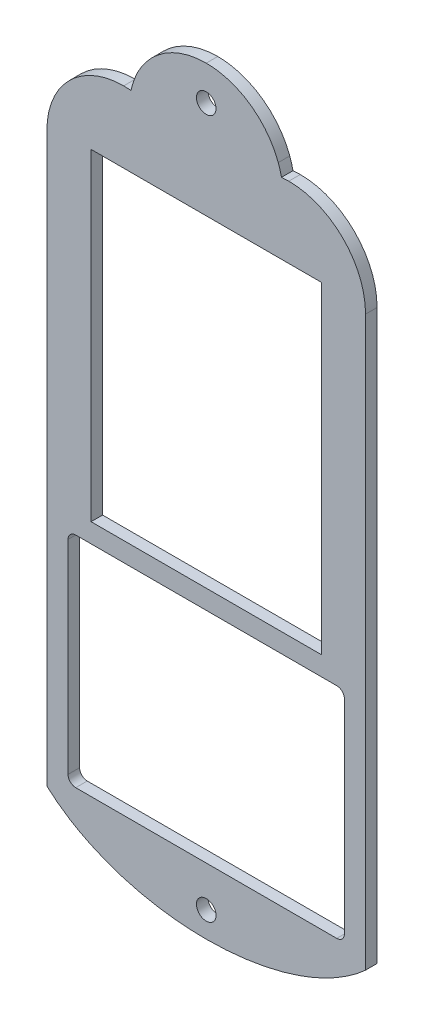
SolidWorks part; units mm, degrees
ref_plane "前视基准面" through (0, 0, 0) normal (0, 0, 1) x (1, 0, 0)
ref_plane "上视基准面" through (0, 0, 0) normal (0, 1, 0) x (1, 0, 0)
ref_plane "右视基准面" through (0, 0, 0) normal (1, 0, 0) x (0, 0, -1)
other "Configuration Table"
sketch "草图1" plane through (0, 0, 0) normal (0, 0, 1) x (1, 0, 0)
  line L0 (-84.75, 68.1509) -> (-84.75, -79.8491)
  line L1 (-1.7484, 68.1509) -> (-1.7484, -79.8491)
  line L2 (-4.2492, 72.5719) -> (-11.3961, 72.5719) construction
  line L3 (-73.2492, 69.5719) -> (-13.2492, 69.5719)
  line L4 (-73.2492, 69.5719) -> (-73.2492, -14.4281)
  line L5 (-73.2492, -14.4281) -> (-13.2492, -14.4281)
  line L6 (-13.2492, 69.5719) -> (-13.2492, -14.4281)
  line L7 (-4.2492, 34.32) -> (-4.2492, 65.5798) construction
  line L8 (-82.2492, 65.5798) -> (-82.2492, 45.884) construction
  line L9 (-4.2492, -36.128) -> (-4.2492, -61.3032) construction
  line L10 (-77.2492, -19.4281) -> (-9.2492, -19.4281)
  line L11 (-79.2492, -21.4281) -> (-79.2492, -74.4281)
  line L12 (-77.2492, -76.4281) -> (-9.2492, -76.4281)
  line L13 (-7.2492, -21.4281) -> (-7.2492, -74.4281)
  line L14 (-7.8227, -79.4281) -> (-4.2492, -79.4281) construction
  line L15 (-82.2492, -52.8839) -> (-82.2492, -72.0269) construction
  circle A0 centre (-43.2492, 95.0101) radius 2.55
  circle A1 centre (-43.2492, -86.9899) radius 2.55
  arc A2 (-79.2492, -74.4281) -> (-77.2492, -76.4281) centre (-77.2492, -74.4281) ccw
  arc A3 (-9.2492, -76.4281) -> (-7.2492, -74.4281) centre (-9.2492, -74.4281) ccw
  arc A4 (-9.2492, -19.4281) -> (-7.2492, -21.4281) centre (-9.2492, -21.4281) cw
  arc A5 (-77.2492, -19.4281) -> (-79.2492, -21.4281) centre (-77.2492, -21.4281) ccw
  spline S0 degree 3 poles (-1.7484, 68.1509) (-1.7484, 79.1964) (-10.7019, 88.1499) (-21.7474, 88.1499) knots 0 0 0 0 1 1 1 1
  spline S1 degree 3 poles (-21.7474, 88.1499) (-22.3894, 88.1499) (-23.028, 88.1181) (-23.6559, 88.0581) knots 1 1 1 1 2 2 2 2
  spline S2 degree 3 poles (-23.6559, 88.0581) (-23.8605, 89.0565) (-24.1427, 90.0302) (-24.4885, 90.9721) knots 2 2 2 2 3 3 3 3
  spline S3 degree 3 poles (-24.4885, 90.9721) (-27.3107, 98.5921) (-34.6449, 104.0249) (-43.2492, 104.0249) knots 3 3 3 3 4 4 4 4
  spline S4 degree 3 poles (-43.2492, 104.0249) (-51.8534, 104.0249) (-59.1877, 98.5921) (-62.0099, 90.9721) knots 4 4 4 4 5 5 5 5
  spline S5 degree 3 poles (-62.0099, 90.9721) (-62.3556, 90.0302) (-62.6379, 89.0565) (-62.8425, 88.0581) knots 5 5 5 5 6 6 6 6
  spline S6 degree 3 poles (-62.8425, 88.0581) (-63.4704, 88.1181) (-64.1054, 88.1499) (-64.7475, 88.1499) knots 6 6 6 6 7 7 7 7
  spline S7 degree 3 poles (-64.7475, 88.1499) (-75.7965, 88.1499) (-84.75, 79.1964) (-84.75, 68.1509) knots 7 7 7 7 8 8 8 8
  spline S8 degree 3 poles (-84.75, -79.8491) (-81.6385, -82.6925) (-77.8179, -85.1972) (-73.447, -87.268) knots 11 11 11 11 12 12 12 12
  spline S9 degree 3 poles (-73.447, -87.268) (-65.0297, -91.2579) (-54.5733, -93.618) (-43.2492, -93.618) knots 12 12 12 12 13 13 13 13
  spline S10 degree 3 poles (-43.2492, -93.618) (-31.925, -93.618) (-21.4687, -91.2579) (-13.0514, -87.268) knots 13 13 13 13 14 14 14 14
  spline S11 degree 3 poles (-13.0514, -87.268) (-8.6805, -85.1972) (-4.8599, -82.6925) (-1.7484, -79.8491) knots 14 14 14 14 15 15 15 15
  dimension "D8" = 2
  dimension "D1" = 3
  dimension "D2" = 9
  dimension "D3" = 9
  dimension "D4" = 5
  dimension "D5" = 3
  dimension "D6" = 3
  dimension "D7" = 3
extrude "凸台-拉伸1" add sketch "草图1" along normal blind 3
